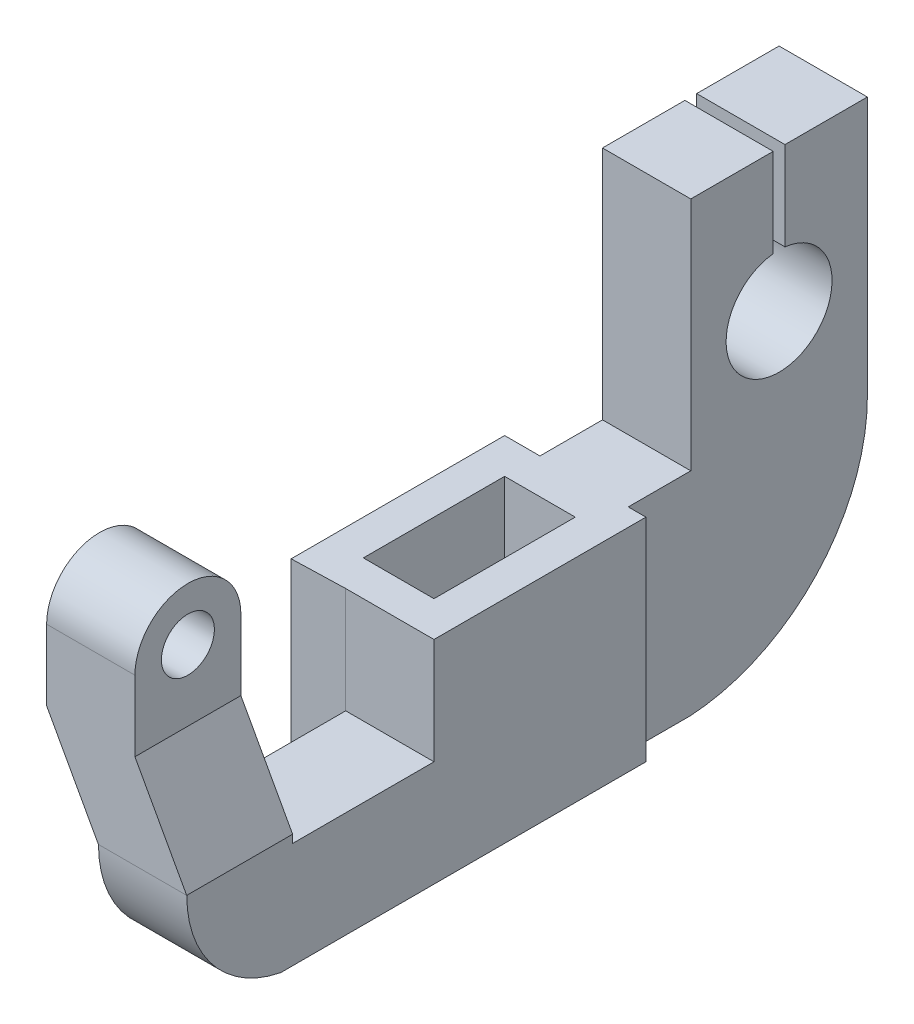
SolidWorks part; units mm, degrees
ref_plane "Front Plane" through (0, 0, 0) normal (0, 0, 1) x (1, 0, 0)
ref_plane "Top Plane" through (0, 0, 0) normal (0, 1, 0) x (1, 0, 0)
ref_plane "Right Plane" through (0, 0, 0) normal (1, 0, 0) x (0, 0, -1)
sketch "Sketch1" plane through (0, 0, 0) normal (1, 0, 0) x (0, 0, -1)
  line L0 (-25.7666, 0) -> (36.2653, 0)
  line L1 (36.2653, 0) -> (36.2653, 36)
  line L2 (36.2653, 36) -> (0.2653, 36)
  line L3 (0.2653, 36) -> (0.2653, 18)
  line L4 (0.2653, 18) -> (-23.7347, 18)
  line L5 (-23.7347, 18) -> (-23.7347, 19.3568)
  line L6 (-23.7347, 19.3568) -> (-41.7347, 19.3568)
  arc A1 (-41.7347, 19.3568) -> (-25.7666, 0) centre (-22.0184, 19.3568) ccw
  dimension "D1" = 78
  dimension "D2" = 24
  dimension "D3" = 18
  dimension "D4" = 18
  dimension "D5" = 36
extrude "Boss-Extrude1" add sketch "Sketch1" against normal blind 15
ref_plane "Plane1" through (0, 0, 23.75) normal (0, 0, 1) x (1, 0, 0)
sketch "Sketch2" plane through (0, 0, 23.75) normal (0, 0, 1) x (1, 0, 0)
  line L0 (-15, 19.3568) -> (-23.7913, 35.3568)
  line L1 (0, 19.3568) -> (-8.7913, 35.3568)
  line L2 (-23.7913, 35.3568) -> (-23.7913, 47.3568)
  line L3 (-8.7913, 35.3568) -> (-8.7913, 47.3568)
  line L4 (-23.7913, 47.3568) -> (-8.7913, 47.3568)
  line L5 (-15, 19.3568) -> (0, 19.3568)
  dimension "D1" = 16
  dimension "D2" = 12
extrude "Boss-Extrude2" add sketch "Sketch2" along normal blind 18
sketch "Sketch3" plane through (-8.7913, 0, 0) normal (1, 0, 0) x (0, 0, -1)
  line L0 (-23.75, 13.2) -> (-23.75, -13.2) construction
  line L1 (-41.75, 47.3568) -> (-23.75, 47.3568)
  arc A0 (-41.75, 47.3568) -> (-23.75, 47.3568) centre (-32.75, 47.3568) cw
extrude "Boss-Extrude3" add sketch "Sketch3" against normal blind 15
sketch "Sketch4" plane through (-8.7913, 0, 0) normal (1, 0, 0) x (0, 0, -1)
  circle A0 centre (-32.75, 47.3568) radius 4.5
extrude "Cut-Extrude1" cut sketch "Sketch4" against normal blind 15
sketch "Sketch5" plane through (0, 36, 0) normal (0, 1, 0) x (1, 0, 0)
  line L0 (-15, 36.2653) -> (-24, 36.2653)
  line L1 (-24, 36.2653) -> (-24, 0)
  line L2 (-24, 0) -> (-15, 0.2653)
  line L3 (-15, 0.2653) -> (0, 0.2653) construction
  line L4 (-15, 0.2653) -> (-15, -23.7347) construction
  line L5 (-15, 0.2653) -> (-15, 36.2653)
  dimension "D1" = 9
extrude "Boss-Extrude4" add sketch "Sketch5" against normal blind 36 separate body
sketch "Sketch6" plane through (0, 36, 0) normal (0, 1, 0) x (1, 0, 0)
  line L0 (0, 36.2653) -> (0, 0.2653) construction
  line L1 (-18, 30.2653) -> (-6, 30.2653)
  line L2 (-18, 30.2653) -> (-18, 6.2653)
  line L3 (-18, 6.2653) -> (-6, 6.2653)
  line L4 (-6, 30.2653) -> (-6, 6.2653)
  line L5 (-24, 36.2653) -> (-24, 0) construction
  line L7 (-15, 36.2653) -> (0, 36.2653) construction
  line L8 (-15, 0.2653) -> (0, 0.2653) construction
  dimension "D1" = 6
  dimension "D2" = 6
  dimension "D3" = 6
  dimension "D4" = 6
extrude "Cut-Extrude2" cut sketch "Sketch6" against normal through all
sketch "Sketch7" plane through (0, 36, 0) normal (0, 1, 0) x (1, 0, 0)
  line L0 (-18, 36.2653) -> (-18, 46.8886)
  line L1 (-15, 36.2653) -> (-24, 36.2653) construction
  line L2 (-18, 46.8886) -> (-3, 46.8886)
  line L3 (-3, 46.8886) -> (-3, 36.2653)
  line L4 (-15, 36.2653) -> (0, 36.2653) construction
  line L5 (-3, 36.2653) -> (-18, 36.2653)
  line L6 (-24, 36.2653) -> (-24, 0) construction
  dimension "D1" = 6
  dimension "D2" = 15
extrude "Boss-Extrude5" add sketch "Sketch7" against normal blind 36
sketch "Sketch9" plane through (-3, 0, 0) normal (1, 0, 0) x (0, 0, -1)
  line L0 (46.8886, 36) -> (46.8886, 76)
  line L1 (46.8886, 76) -> (76.8886, 76)
  line L2 (76.8886, 76) -> (76.8886, 31.9374)
  line L3 (46.8886, 0) -> (46.8886, 36) construction
  line L4 (46.8886, 36) -> (46.8886, 0)
  line L5 (60.8886, 76) -> (60.8886, 60.9443)
  line L6 (62.8886, 76) -> (62.8886, 60.9443)
  arc A0 (76.8886, 31.9374) -> (46.8886, 0) centre (44.8886, 31.9374) cw
  circle A1 centre (61.8886, 52) radius 9
  point P12 (61.8886, 76)
  line M10 (46.8886, 0) -> (46.8886, 36)
  dimension "D1" = 76
  dimension "D2" = 32
  dimension "D4" = 18
  dimension "D3" = 30
  dimension "D5" = 24
  dimension "D6" = 14
  dimension "D7" = 14
extrude "Boss-Extrude6" add sketch "Sketch9" against normal blind 15 contours A1 L5 L1 L0 A0 L2 L6 M10
